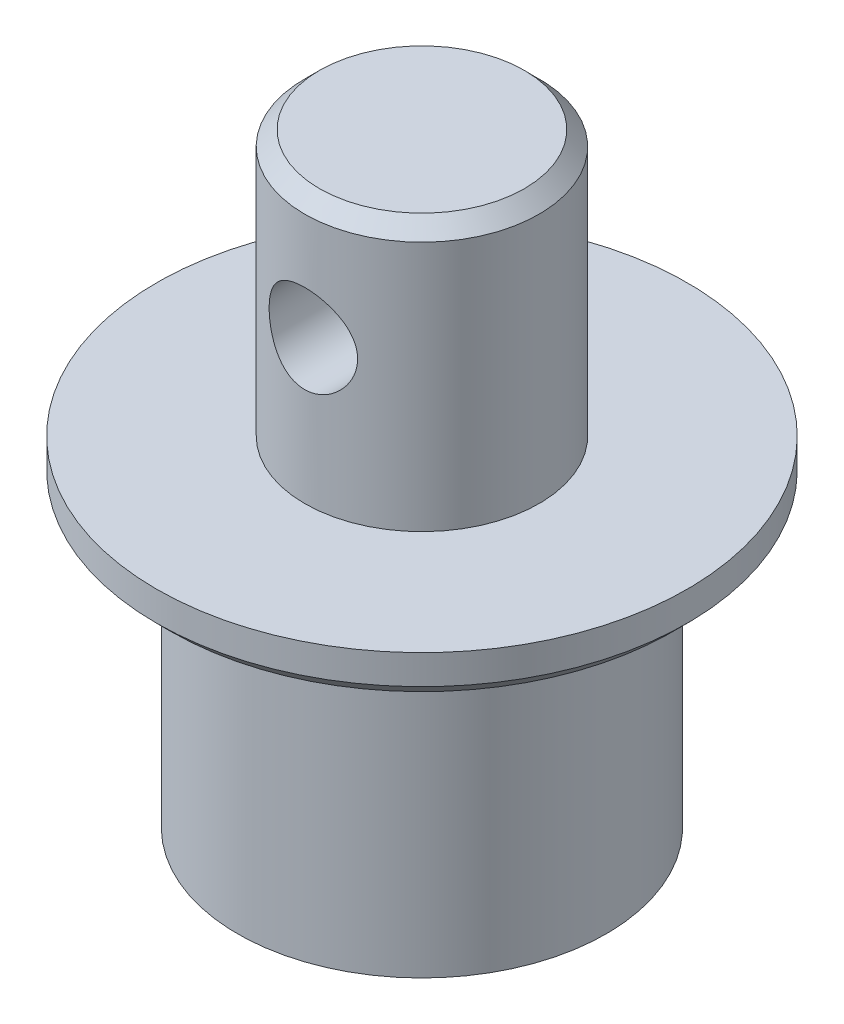
SolidWorks part; units mm, degrees
material "普通碳钢"
ref_plane "前视基准面" through (0, 0, 0) normal (0, 0, 1) x (1, 0, 0)
ref_plane "上视基准面" through (0, 0, 0) normal (0, 1, 0) x (1, 0, 0)
ref_plane "右视基准面" through (0, 0, 0) normal (1, 0, 0) x (0, 0, -1)
sketch "草图1" plane through (0, 0, 0) normal (0, 1, 0) x (1, 0, 0)
  circle A0 centre (0, 0) radius 7.95
  dimension "D1" = 15.9
extrude "凸台-拉伸1" add sketch "草图1" along normal blind 18 contours A0
chamfer "倒角2" distance 1 angle 45 1 edges at (0, 18, 7.95)
sketch "草图4" plane through (0, 0, 0) normal (0, 1, 0) x (1, 0, 0)
  circle A0 centre (0, 0) radius 18
extrude "凸台-拉伸2" add sketch "草图4" against normal blind 3
chamfer "倒角1" distance 1 angle 45 1 edges at (0, -3, 18)
ref_plane "基准面4" through (0, -3, 0) normal (0, -1, 0) x (-1, 0, 0)
sketch "草图5" plane through (0, -3, 0) normal (0, -1, 0) x (-1, 0, 0)
  circle A0 centre (0, 0) radius 12.5
extrude "凸台-拉伸3" add sketch "草图5" along normal blind 20
ref_plane "基准面5" through (0, -23, 0) normal (0, -1, 0) x (-1, 0, 0)
sketch "草图9" plane through (0, 0, 0) normal (0, 0, 1) x (1, 0, 0)
  line L0 (0, -19.8) -> (0, 19.8) construction
  line L1 (19.8, 0) -> (-19.8, 0) construction
  circle A0 centre (0, 9.7) radius 3
  dimension "D1" = 9.7
  dimension "D2" = 6
extrude "切除-拉伸2" cut sketch "草图9" against normal through all both and the other way through all
sketch "草图10" plane through (0, -3, 0) normal (0, -1, 0) x (-1, 0, 0)
  circle A0 centre (0, 0) radius 7.95
extrude "切除-拉伸3" cut sketch "草图10" along normal up to surface (10 mm away) from offset 10 up to face at (0, -23, -12.5)
